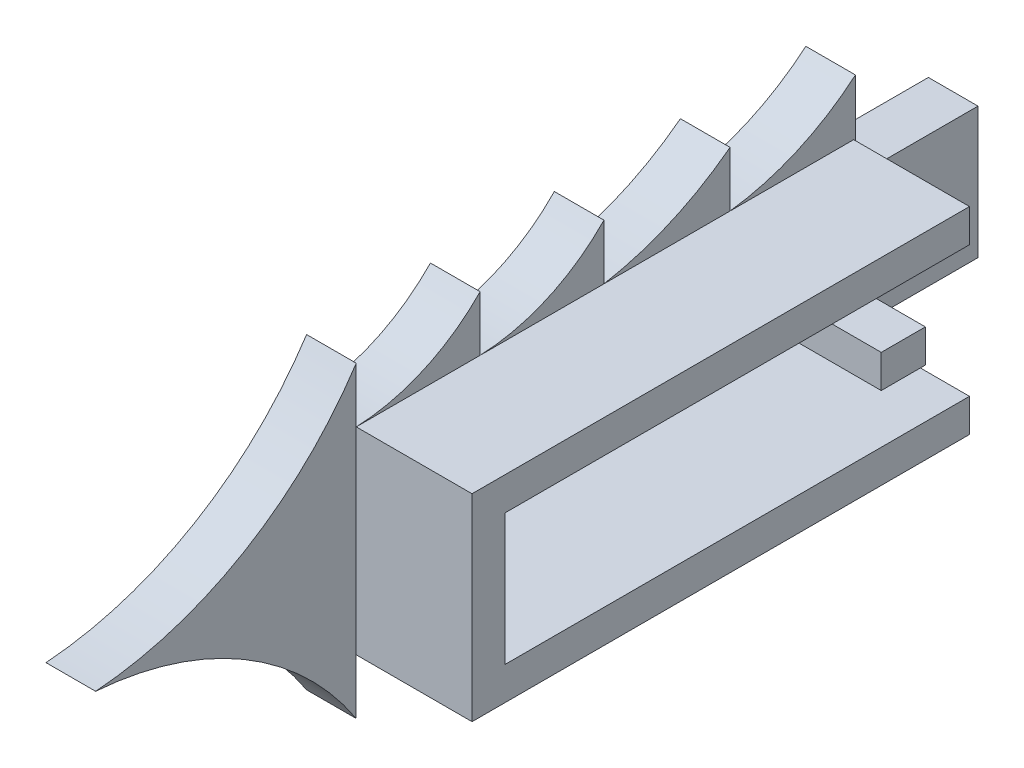
SolidWorks part; units mm, degrees
ref_plane "Front Plane" through (0, 0, 0) normal (1, 0, 0) x (0, 1, 0)
ref_plane "Top Plane" through (0, 0, 0) normal (0, 0, 1) x (0, 1, 0)
ref_plane "Right Plane" through (0, 0, 0) normal (0, 1, 0) x (-1, 0, 0)
sketch "Sketch1" plane through (0, 0, 0) normal (1, 0, 0) x (0, 1, 0)
  line L0 (-5.95, 3.8) -> (5.95, 3.8) construction
  line L1 (0, 0) -> (0, 3.8) construction
  line L2 (-1.5, -30.3) -> (1.5, -30.3) construction
  line L3 (0, -30.3) -> (0, -1.5) construction
  line L4 (-5.95, 3.8) -> (-5.95, -38.3) construction
  line L5 (5.95, 3.8) -> (5.95, -38.3) construction
  line L6 (5.95, -38.3) -> (1.5, -38.3) construction
  line L7 (1.5, -38.3) -> (1.5, -30.3) construction
  line L8 (-1.5, -30.3) -> (-1.5, -38.3) construction
  line L9 (-1.5, -38.3) -> (-5.95, -38.3) construction
  line L11 (-1.5, -30.3) -> (1.5, -30.3)
  line L12 (-1.5, -30.3) -> (-1.5, -34.3)
  line L13 (-1.5, -34.3) -> (1.5, -34.3)
  line L14 (1.5, -30.3) -> (1.5, -34.3)
  line L15 (5.95, -38.3) -> (8.95, -38.3)
  line L16 (5.95, -38.3) -> (5.95, 3.8)
  line L17 (5.95, 3.8) -> (8.95, 3.8)
  line L18 (8.95, -38.3) -> (8.95, 3.8)
  line L19 (8.95, 3.8) -> (-8.95, 3.8)
  line L20 (8.95, 3.8) -> (8.95, 6.8)
  line L21 (8.95, 6.8) -> (-8.95, 6.8)
  line L22 (-8.95, 3.8) -> (-8.95, 6.8)
  line L23 (-5.95, -38.3) -> (-8.95, -38.3)
  line L24 (-5.95, -38.3) -> (-5.95, 3.8)
  line L25 (-5.95, 3.8) -> (-8.95, 3.8)
  line L26 (-8.95, -38.3) -> (-8.95, 3.8)
  circle A0 centre (0, 0) radius 1.5 construction
  dimension "D1" = 3
  dimension "D2" = 3.8
  dimension "D3" = 11.9
  dimension "D4" = 34.1
  dimension "D5" = 3
  dimension "D6" = 8
  dimension "D7" = 3
  dimension "D8" = 3
  dimension "D9" = 3
extrude "Boss-Extrude1" add sketch "Sketch1" along normal blind 12 contours L22 L19 L17 L20 L21 | L26 L23 L24 L19 | L15 L18 L17 L16 | L12 L11 L14 L13
ref_plane "Plane1" through (12, 8.95, 6.8) normal (0, 0, 1) x (1, 0, 0)
sketch "Sketch3" plane through (0, 0, 0) normal (-1, 0, 0) x (0, 0, 1)
  line L0 (6.8, -3.4525) -> (6.8, 21.3525) construction
  line L1 (-38.3, -8.95) -> (6.8, -8.95)
  line L2 (-38.3, -8.95) -> (-38.3, 8.95)
  line L3 (-38.3, 8.95) -> (6.8, 8.95)
  line L4 (6.8, -8.95) -> (6.8, 8.95)
  line L5 (-38.3, 8.95) -> (6.8, 8.95) construction
  circle A0 centre (0, 0) radius 1.5
extrude "Boss-Extrude2" add sketch "Sketch3" along normal blind 3
sketch "Sketch5" plane through (-3, 0, 0) normal (-1, 0, 0) x (0, -1, 0)
  line L0 (-8.95, -38.3) -> (-8.95, 3.8) construction
  line L1 (-13.95, -49.5728) -> (13.95, -49.5728)
  line L2 (-13.95, -49.5728) -> (-13.95, 21.5835)
  line L4 (13.95, -49.5728) -> (13.95, 20.9272)
  line L5 (8.95, -38.3) -> (8.95, 3.8) construction
  line L8 (-13.95, 21.5835) -> (-13.95, 30.4272)
  line L9 (-13.95, 30.4272) -> (13.95, 30.4272)
  line L10 (13.95, 20.9272) -> (13.95, 30.4272)
  dimension "D1" = 5
  dimension "D2" = 5
  dimension "D3" = 9.5
  dimension "D4" = 80
extrude "Boss-Extrude4" add sketch "Sketch5" against normal blind 4.5
sketch "Sketch6" plane through (-3, 0, 0) normal (-1, 0, 0) x (0, -1, 0)
  line L0 (0, 30.4272) -> (0, -49.5728) construction
  line L1 (-13.95, 30.4272) -> (13.95, 30.4272) construction
  line L2 (-13.95, -49.5728) -> (13.95, -49.5728) construction
  line L3 (-13.95, -49.5728) -> (-13.95, 30.4272) construction
  line L4 (3.4525, 6.8) -> (-21.3525, 6.8) construction
  line L5 (-13.95, -49.5728) -> (-13.95, 30.4272) construction
  line L6 (-8.95, -38.3) -> (-8.95, 6.8) construction
  line L7 (-8.95, 6.8) -> (-8.95, -38.3) construction
  line L8 (-8.95, -4.4306) -> (-13.95, -4.4306)
  line L9 (-13.95, -15.6611) -> (-8.95, -15.6611)
  line L10 (-13.95, -27.0926) -> (-8.95, -27.0926)
  line L11 (-13.95, -38.4631) -> (-5.95, -38.4631)
  line L12 (-5.95, -38.4631) -> (-5.95, -49.5728)
  line L13 (-5.95, -38.3) -> (-5.95, -49.5728) construction
  line L14 (-13.95, -49.5728) -> (13.95, -49.5728) construction
  line L15 (-8.95, 6.8) -> (-13.95, 6.8)
  line L16 (0, 30.4272) -> (0, 38.2073)
  line L17 (0, 38.2073) -> (-27.4952, 38.2073)
  line L18 (-27.4952, 38.2073) -> (-27.4952, -49.5728)
  line L19 (-27.4952, -49.5728) -> (-5.95, -49.5728)
  arc A2 (-13.95, 6.8) -> (0, 30.4272) centre (-30.8955, 32.7368) ccw
  arc A3 (-13.95, -4.4306) -> (-8.95, 6.8) centre (-25.4501, 7.4177) ccw
  arc A4 (-13.95, -15.6611) -> (-8.95, -4.4306) centre (-25.4501, -3.8128) ccw
  arc A5 (-8.95, -15.6611) -> (-13.95, -27.0926) centre (-34.922, -11.1105) cw
  arc A6 (-8.95, -27.0926) -> (-13.95, -38.4631) centre (-30.5316, -24.387) cw
extrude "Cut-Extrude4" cut sketch "Sketch6" against normal through all both and the other way through all
mirror "Mirror1" about plane through (0, 0, 0) normal (0, 1, 0) of "Cut-Extrude4"
